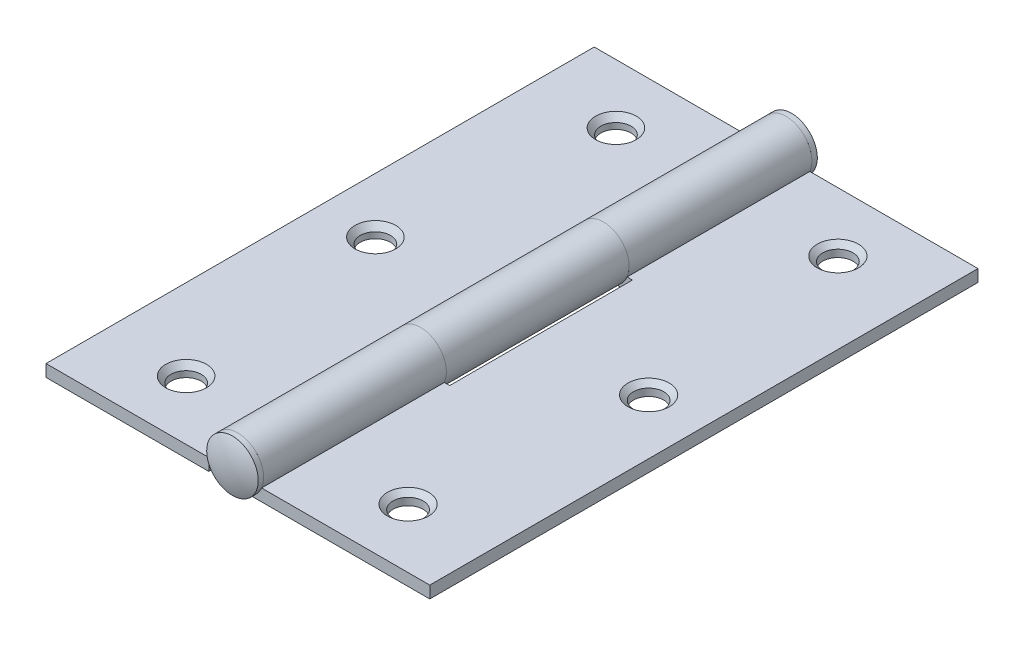
SolidWorks part; units mm, degrees
ref_plane "Front Plane" through (0, 0, 0) normal (0, 0, 1) x (1, 0, 0)
ref_plane "Top Plane" through (0, 0, 0) normal (0, 1, 0) x (1, 0, 0)
ref_plane "Right Plane" through (0, 0, 0) normal (1, 0, 0) x (0, 0, -1)
sketch "Sketch1" plane through (0, 0, 0) normal (0, 0, 1) x (1, 0, 0)
  line L0 (22.225, -2.5661) -> (1.524, -2.5661)
  line L1 (22.225, -2.5661) -> (22.225, -1.1691)
  line L2 (22.225, -1.1691) -> (2.746, -1.1691)
  line L3 (1.524, -2.5661) -> (1.524, 0) construction
  line L4 (-2.9845, 0) -> (-2.9845, -2.5661) construction
  line L5 (-22.225, -1.1691) -> (-3.3655, -1.1691)
  line L6 (-22.225, -1.1691) -> (-22.225, -2.5661)
  line L7 (-22.225, -2.5661) -> (-3.3655, -2.5661)
  line L8 (-3.3655, -1.1691) -> (-3.3655, -2.5661)
  line L9 (-2.9845, -2.5661) -> (-2.9845, -21.4256) construction
  circle A0 centre (0, 0) radius 1.524
  arc A1 (1.524, -2.5661) -> (2.746, -1.1691) centre (0, 0) cw
  point P5 (-1.524, 0)
  point P15 (2.9845, 0)
  point P16 (-22.225, -2.5661)
  point P17 (22.225, -2.5661)
  point P18 (1.524, 0)
  point P19 (1.524, 0)
  point P21 (22.225, -1.1691)
  point P22 (-22.225, -1.1691)
  point P24 (-2.9845, 0)
  dimension "knuckle dia" = 5.969
  dimension "Leaf Thickness" = 1.397
  dimension "D3" = 0.381
  dimension "Overall Width" = 44.45
  dimension "Range of Motion" = 270
sketch "Sketch2" plane through (0, 0, 0) normal (1, 0, 0) x (0, 0, -1)
  line L0 (-31.75, 0) -> (31.75, 0)
  point P2 (0, 0)
  point P6 (31.75, 0)
  point P7 (-31.75, 0)
  dimension "Frame Leaf Height" = 63.5
ref_plane "Plane1" through (0, -2.5661, 0) normal (0, 1, 0) x (1, 0, 0)
sketch "Sketch3" plane through (0, -2.5661, 0) normal (0, 1, 0) x (1, 0, 0)
  line L0 (-15.8242, 0) -> (15.8242, 0) construction
  line L1 (22.225, -31.75) -> (-22.225, -31.75)
  line L2 (22.225, -31.75) -> (22.225, 31.75)
  line L3 (22.225, 31.75) -> (-22.225, 31.75)
  line L4 (-22.225, -31.75) -> (-22.225, 31.75)
  line L5 (-12.8524, 24.892) -> (12.8524, 24.892) construction
  line L6 (-12.8524, 24.892) -> (-12.8524, -24.892) construction
  line L7 (-12.8524, -24.892) -> (12.8524, -24.892) construction
  line L8 (12.8524, 24.892) -> (12.8524, -24.892) construction
  circle A0 centre (-12.8524, 24.892) radius 1.7526
  circle A1 centre (12.8524, 24.892) radius 1.7526
  circle A2 centre (12.8524, -24.892) radius 1.7526
  circle A3 centre (-12.8524, -24.892) radius 1.7526
  circle A4 centre (15.8242, 0) radius 1.7526
  circle A5 centre (-15.8242, 0) radius 1.7526
  point P0 (0, 0)
  point P6 (-22.225, 0)
  point P7 (15.8242, 0)
  point P14 (12.8524, 0)
  point P15 (0, 24.892)
  point P20 (0, -31.75)
  point P21 (-22.225, 31.75)
  point P22 (22.225, 31.75)
  point P23 (22.225, -31.75)
  point P24 (-22.225, -31.75)
  point P25 (-12.8524, -24.892)
  point P26 (12.8524, -24.892)
  point P27 (12.8524, 24.892)
  point P28 (-12.8524, 24.892)
  point P29 (22.225, 0)
  point P30 (0, 31.75)
  point P31 (-15.8242, 0)
  point P34 (0, 0)
  dimension "Mounting Hole Dia" = 3.5052
  dimension "CTC Corner Hole Ht" = 49.784
  dimension "Corner Hole Wd" = 12.8524
  dimension "Center Hole Ht" = 24.892
  dimension "Center Hole Wd" = 15.8242
  dimension "Hole to Edge" = 6.858
sketch "Sketch4" plane through (0, 0, 0) normal (0, 0, 1) x (1, 0, 0)
  line L0 (-22.225, -1.1691) -> (-22.225, -2.5661) construction
  line L1 (-22.225, -2.5661) -> (-3.3655, -2.5661) construction
  line L2 (-3.3655, -1.1691) -> (-3.3655, -2.5661) construction
  line L3 (-22.225, -1.1691) -> (-3.3655, -1.1691) construction
  line L4 (22.225, -2.5661) -> (22.225, -1.1691) construction
  line L5 (22.225, -2.5661) -> (1.524, -2.5661) construction
  line L6 (22.225, -1.1691) -> (2.746, -1.1691) construction
  line L7 (-22.225, -1.1691) -> (-22.225, -2.5661)
  line L8 (-22.225, -2.5661) -> (-3.3655, -2.5661)
  line L9 (-3.3655, -1.1691) -> (-3.3655, -2.5661)
  line L10 (-22.225, -1.1691) -> (-3.3655, -1.1691)
  line L11 (22.225, -2.5661) -> (22.225, -1.1691)
  line L12 (22.225, -2.5661) -> (1.524, -2.5661)
  line L13 (22.225, -1.1691) -> (2.746, -1.1691)
  circle A0 centre (0, 0) radius 1.524 construction
  arc A1 (2.746, -1.1691) -> (1.524, -2.5661) centre (0, 0) ccw construction
  circle A2 centre (0, 0) radius 1.524
  arc A3 (2.746, -1.1691) -> (1.524, -2.5661) centre (0, 0) ccw
extrude "Boss-Extrude1" add sketch "Sketch4" against normal up to vertex (31.75 mm away) and the other way up to vertex (31.75 mm away) up to point (-22.225, -2.5661, -31.75) other way up to point (-22.225, -2.5661, 31.75)
sketch "Sketch5" plane through (0, 0, 0) normal (0, 1, 0) x (1, 0, 0)
  line L0 (0, 33.0073) -> (0, 31.75) construction
  line L1 (-2.9845, 32.3787) -> (-2.9845, 31.75)
  line L2 (22.225, 31.75) -> (-22.225, 31.75) construction
  line L3 (-2.9845, 31.75) -> (-1.524, 31.75)
  line L4 (-1.524, 31.75) -> (-1.524, -31.75)
  line L5 (22.225, -31.75) -> (-22.225, -31.75) construction
  line L6 (-1.524, -31.75) -> (-2.9845, -31.75)
  line L7 (-2.9845, -31.75) -> (-2.9845, -32.3787)
  line L8 (0, 33.0073) -> (0, -33.0073)
  line L9 (-2.9845, 0) -> (-2.9845, 31.75) construction
  line L10 (-2.9845, 0) -> (2.9845, 0) construction
  line L11 (-2.9845, 0) -> (0, 0) construction
  line L12 (-2.9845, -31.75) -> (-1.524, -31.75)
  line L13 (-2.9845, -32.3787) -> (-2.9845, -31.75)
  circle A0 centre (0, 32.3787) radius 0.6287 construction
  arc A1 (-2.9845, 32.3787) -> (0, 33.0073) centre (0, 25.6086) cw
  arc A2 (-2.9845, -32.3787) -> (0, -33.0073) centre (0, -25.6086) ccw
  point P2 (0, 33.0073)
  point P20 (0, 0)
  point P21 (-1.524, 0)
  dimension "D1" = 1.2573
  dimension "D3" = 63.5
revolve "Revolve1" add sketch "Sketch5" angle 360 about L8
sketch "Sketch6" plane through (0, -1.1691, 0) normal (0, 1, 0) x (1, 0, 0)
  circle A0 centre (-12.8524, 24.892) radius 1.7526 construction
  circle A1 centre (-12.8524, -24.892) radius 1.7526 construction
  circle A2 centre (12.8524, -24.892) radius 1.7526 construction
  circle A3 centre (12.8524, 24.892) radius 1.7526 construction
  circle A4 centre (-12.8524, 24.892) radius 1.7526
  circle A5 centre (-12.8524, -24.892) radius 1.7526
  circle A6 centre (12.8524, -24.892) radius 1.7526
  circle A7 centre (12.8524, 24.892) radius 1.7526
  circle A8 centre (15.8242, 0) radius 1.7526 construction
  circle A9 centre (15.8242, 0) radius 1.7526
  circle A10 centre (-15.8242, 0) radius 1.7526 construction
  circle A11 centre (-15.8242, 0) radius 1.7526
extrude "Cut-Extrude1" cut sketch "Sketch6" against normal blind 2.54
chamfer "Chamfer1" distance 0.6985 angle 41 3 edges at (-14.605, -1.1691, -24.892) (-14.605, -1.1691, 24.892) (-17.5768, -1.1691, 0)
chamfer "Chamfer2" distance 0.635 angle 41 3 edges at (11.0998, -1.1691, 24.892) (11.0998, -1.1691, -24.892) (14.0716, -1.1691, 0)
sketch "Sketch8" plane through (0, -1.1691, 0) normal (0, 1, 0) x (1, 0, 0)
  line L0 (-3.3655, 31.75) -> (-3.3655, -31.75) construction
  line L1 (-3.3655, 10.5833) -> (3.3655, 10.5833)
  line L2 (-3.3655, 10.5833) -> (-3.3655, -10.5833)
  line L3 (-3.3655, -10.5833) -> (3.3655, -10.5833)
  line L4 (3.3655, 10.5833) -> (3.3655, -10.5833)
  line L5 (0, 31.75) -> (0, 10.5833) construction
  line L6 (0, -10.5833) -> (0, -31.75) construction
  point P6 (0, 10.5833)
extrude "Cut-Extrude2" cut sketch "Sketch8" against normal through all both and the other way through all
sketch "Sketch9" plane through (0, 0, 0) normal (0, 0, 1) x (1, 0, 0)
  line L0 (-3.3655, -2.5661) -> (-1.524, -2.5661)
  line L1 (-2.746, -1.1691) -> (-3.3655, -1.1691)
  line L3 (-3.3655, -1.1691) -> (-3.3655, -2.5661)
  circle A0 centre (0, 0) radius 1.524 construction
  circle A1 centre (0, 0) radius 1.524
  arc A2 (2.746, -1.1691) -> (1.524, -2.5661) centre (0, 0) ccw construction
  arc A3 (2.746, -1.1691) -> (-2.746, -1.1691) centre (0, 0) ccw
  arc A4 (-1.524, -2.5661) -> (1.524, -2.5661) centre (0, 0) ccw
  arc A5 (2.746, -1.1691) -> (1.524, -2.5661) centre (0, 0) cw
extrude "Boss-Extrude2" add sketch "Sketch9" against normal up to surface and the other way up to surface separate body up to face at (1.6549, -0.9094, -10.5833) other way up to face at (1.6549, -0.9094, 10.5833)
combine bodies "Combine1" operation type add bodies to combine 143 140
equation "\"Overall Width@Sketch1\"=\"Frame Leaf Width@Sketch1\"*2"
equation "\"D1@Sketch5\" = \"Leaf Thickness@Sketch1\" * .9"
equation "\"D1@Chamfer1\" = \"Leaf Thickness@Sketch1\" * .5"
